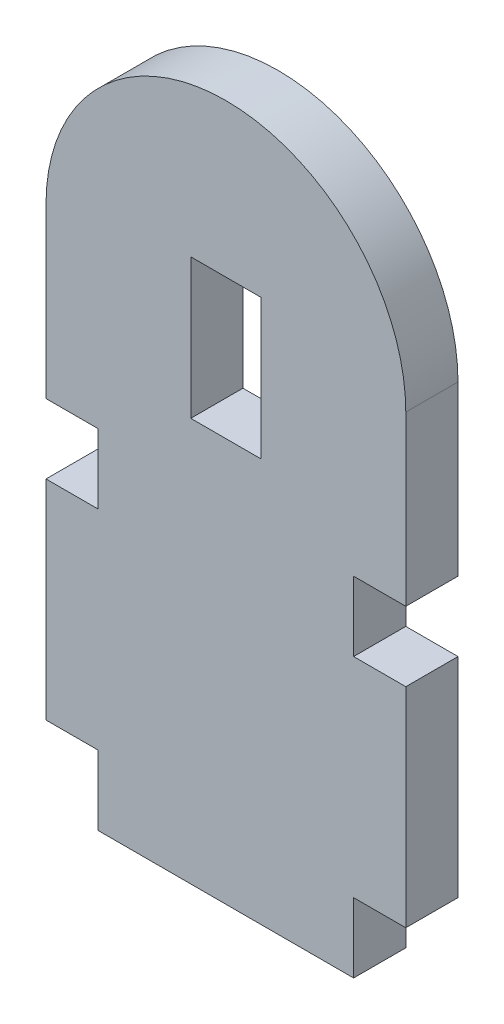
SolidWorks part; units mm, degrees
ref_plane "Plan de face" through (0, 0, 0) normal (0, 0, 1) x (1, 0, 0)
ref_plane "Plan de dessus" through (0, 0, 0) normal (0, 1, 0) x (1, 0, 0)
ref_plane "Plan de droite" through (0, 0, 0) normal (1, 0, 0) x (0, 0, -1)
sketch "Esquisse1" plane through (0, 0, 0) normal (0, 0, 1) x (1, 0, 0)
  line L0 (-35.2493, -55) -> (-35.2493, -75)
  line L1 (-35.2493, -75) -> (38.1407, -75)
  line L2 (-50.2493, -55) -> (-50.2493, 5)
  line L3 (53.1407, 5) -> (38.1407, 5)
  line L4 (53.1407, -55) -> (53.1407, 5)
  line L7 (53.1407, -55) -> (38.1407, -55)
  line L8 (-50.2493, -55) -> (-35.2493, -55)
  line L9 (1.4457, 73.3267) -> (1.4457, -76.6733) construction
  line L11 (53.1407, 5) -> (38.1407, 5)
  line L12 (53.1407, 25) -> (38.1407, 25)
  line L13 (38.1407, 5) -> (38.1407, 25)
  line L14 (38.1407, -55) -> (38.1407, -75)
  line L15 (53.1407, 25) -> (53.1407, 73.3267)
  line L16 (-50.2493, 5) -> (-35.2493, 5)
  line L17 (-50.2493, 25) -> (-35.2493, 25)
  line L18 (-35.2493, 5) -> (-35.2493, 25)
  line L19 (-50.2493, 25) -> (-50.2493, 73.3267)
  line L20 (-8.6543, 40.8828) -> (11.5457, 40.8828)
  line L21 (-8.6543, 40.8828) -> (-8.6543, 81.0828)
  line L22 (-8.6543, 81.0828) -> (11.5457, 81.0828)
  line L23 (11.5457, 40.8828) -> (11.5457, 81.0828)
  line L24 (-8.6543, 40.8828) -> (11.5457, 81.0828) construction
  line L25 (-8.6543, 81.0828) -> (11.5457, 40.8828) construction
  arc A0 (53.1407, 73.3267) -> (-50.2493, 73.3267) centre (1.4457, 73.3267) ccw
  circle A1 centre (1.4457, 73.3267) radius 5
  point P0 (0, 0)
  point P24 (1.4457, 60.9828)
  dimension "D3" = 60
  dimension "D9" = 10
  dimension "D10" = 40.2
  dimension "D2" = 103.39
  dimension "D4" = 20
  dimension "D5" = 20
  dimension "D6" = 15
  dimension "D7" = 15
  dimension "D11" = 20.2
extrude "Boss.-Extru.1" add sketch "Esquisse1" along normal blind 15 contours L11 L13 L12 L15 A0 L19 L17 L18 L16 L2 L8 L0 L1 L14 L7 L4 | L21 L22 L23 L20
